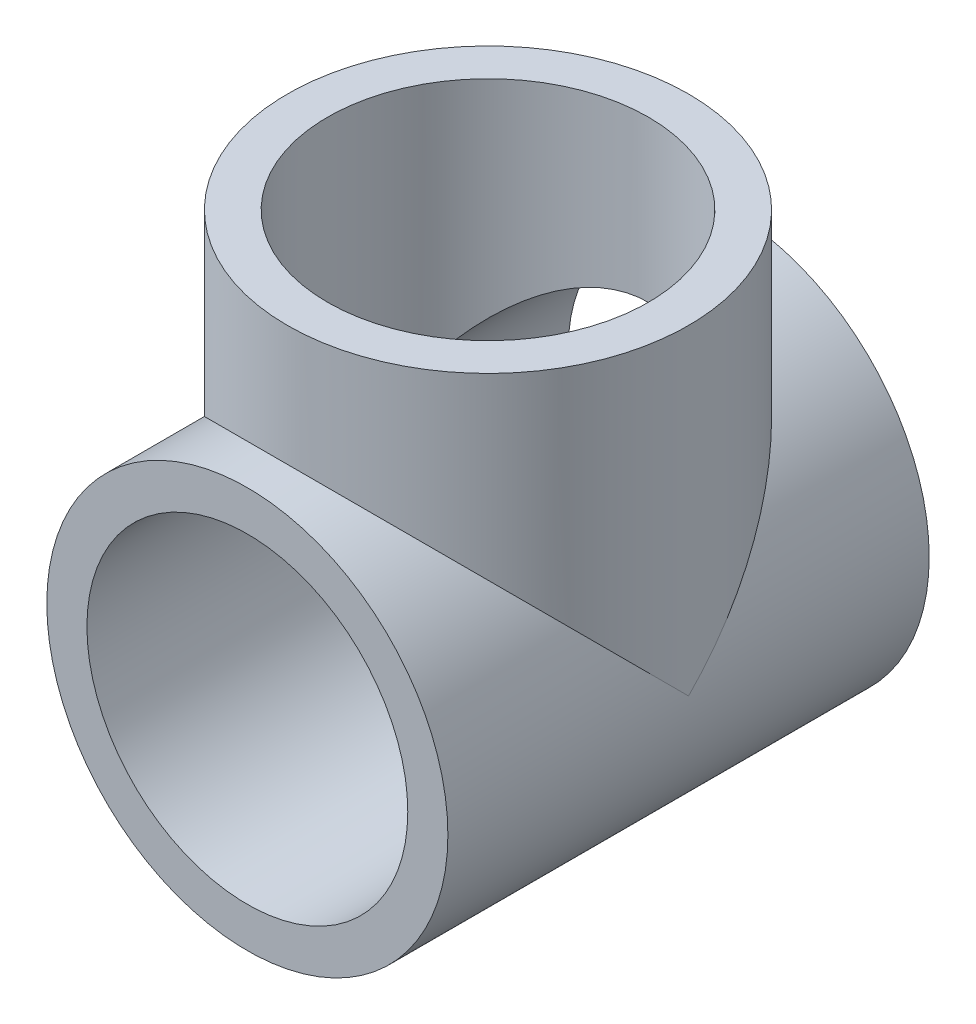
SolidWorks part; units mm, degrees
ref_plane "前视基准面" through (0, 0, 0) normal (0, 0, 1) x (1, 0, 0)
ref_plane "上视基准面" through (0, 0, 0) normal (0, 1, 0) x (1, 0, 0)
ref_plane "右视基准面" through (0, 0, 0) normal (1, 0, 0) x (0, 0, -1)
sketch "草图1" plane through (0, 0, 0) normal (0, 0, 1) x (1, 0, 0)
  circle A0 centre (0, 0) radius 10
  circle A1 centre (0, 0) radius 12.5
  dimension "D1" = 20
  dimension "D2" = 25
extrude "凸台-拉伸1" add sketch "草图1" along normal mid plane 30
ref_plane "基准面1" through (0, 20, 0) normal (0, 1, 0) x (1, 0, 0)
sketch "草图2" plane through (0, 20, 0) normal (0, 1, 0) x (1, 0, 0)
  circle A0 centre (0, 0) radius 10
  circle A1 centre (0, 0) radius 12.5
  dimension "D1" = 25
  dimension "D2" = 20
extrude "凸台-拉伸2" add sketch "草图2" against normal up to surface (7.5 mm away)
sketch "草图3" plane through (0, 20, 0) normal (0, 1, 0) x (1, 0, 0)
  circle A0 centre (0, 0) radius 10
extrude "切除-拉伸1" cut sketch "草图3" against normal blind 20
